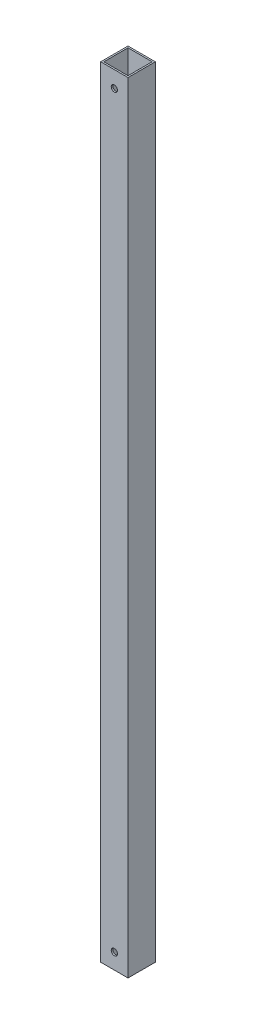
SolidWorks part; units mm, degrees
material "AISI 1020"
ref_plane "Plan de face" through (0, 0, 0) normal (0, 0, 1) x (1, 0, 0)
ref_plane "Plan de dessus" through (0, 0, 0) normal (0, 1, 0) x (1, 0, 0)
ref_plane "Plan de droite" through (0, 0, 0) normal (1, 0, 0) x (0, 0, -1)
sketch "Croquis1" plane through (0, 0, 0) normal (0, 1, 0) x (1, 0, 0)
  line L0 (2, 2) -> (2, 33)
  line L1 (0, 0) -> (35, 0)
  line L2 (0, 0) -> (0, 35)
  line L3 (0, 35) -> (35, 35)
  line L4 (35, 0) -> (35, 35)
  line L5 (2, 33) -> (33, 33)
  line L6 (33, 2) -> (33, 33)
  line L7 (2, 2) -> (33, 2)
  dimension "D1" = 35
  dimension "D2" = 2
extrude "Saliente-Extruir1" add sketch "Croquis1" along normal blind 1000
sketch "Croquis2" plane through (0, 0, 0) normal (0, 0, 1) x (1, 0, 0)
  line L0 (0, 0) -> (35, 0) construction
  circle A0 centre (17.5, 20) radius 4
  dimension "D1" = 8
  dimension "D2" = 20
extrude "Cortar-Extruir1" cut sketch "Croquis2" against normal blind 35
sketch "Croquis3" plane through (0, 0, -35) normal (0, 0, -1) x (-1, 0, 0)
  line L0 (-35, 1000) -> (0, 1000) construction
  circle A0 centre (-17.5, 979) radius 4
  dimension "D1" = 8
  dimension "D2" = 21
extrude "Cortar-Extruir2" cut sketch "Croquis3" against normal blind 35
